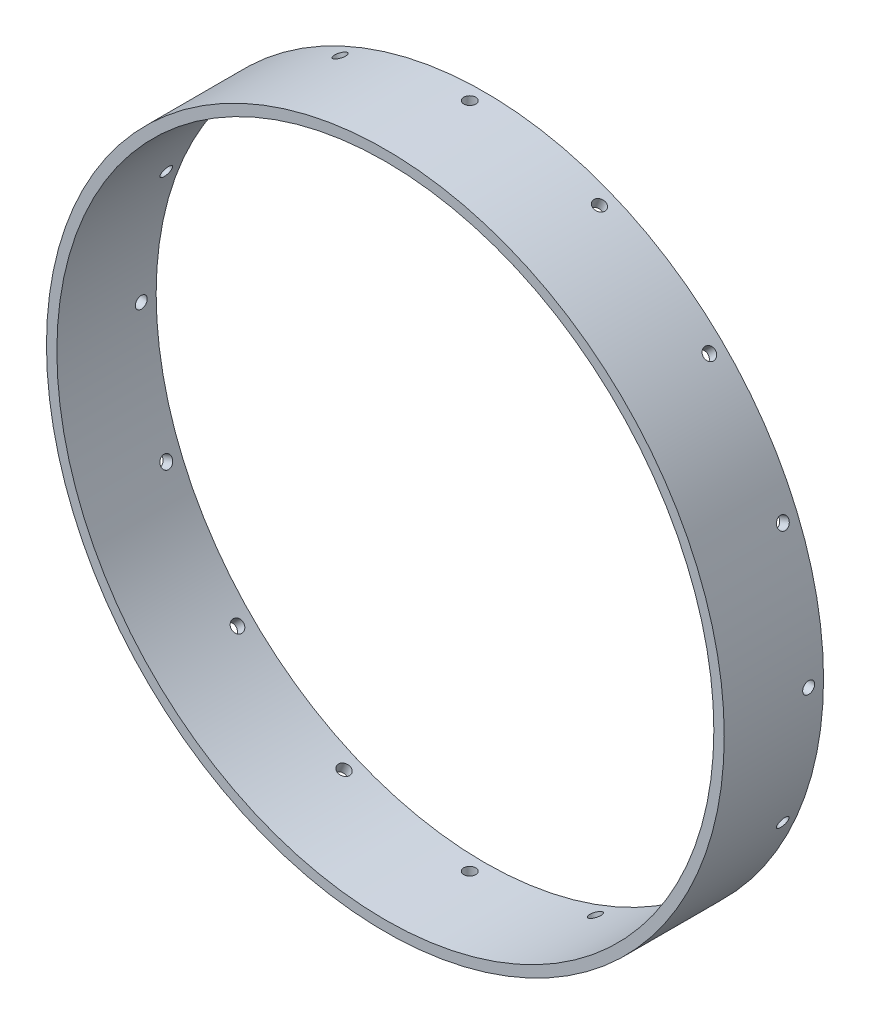
SolidWorks part; units mm, degrees
material "AISI 316 Annealed Stainless Steel Bar (SS)"
ref_plane "Front Plane" through (0, 0, 0) normal (1, 0, 0) x (0, 1, 0)
ref_plane "Top Plane" through (0, 0, 0) normal (0, 0, 1) x (0, 1, 0)
ref_plane "Right Plane" through (0, 0, 0) normal (0, 1, 0) x (-1, 0, 0)
sketch "Sketch1" plane through (0, 0, 0) normal (0, 0, 1) x (0, 1, 0)
  circle A0 centre (0, 0) radius 132.334
  circle A1 centre (0, 0) radius 136.525
  dimension "D1" = 264.668
  dimension "D2" = 273.05
extrude "Boss-Extrude1" add sketch "Sketch1" along normal blind 40
sketch "Sketch2" plane through (0, 0, 0) normal (1, 0, 0) x (0, 1, 0)
  line L0 (0, 6) -> (0, 0) construction
  circle A0 centre (0, 6) radius 2.413
  dimension "D1" = 4.826
  dimension "D2" = 6
extrude "Cut-Extrude1" cut sketch "Sketch2" along normal through all contours A0
pattern_circular "CirPattern1" count 16 over 360 about axis through (0, 0, 40) along (0, 0, -1) of "Cut-Extrude1"
